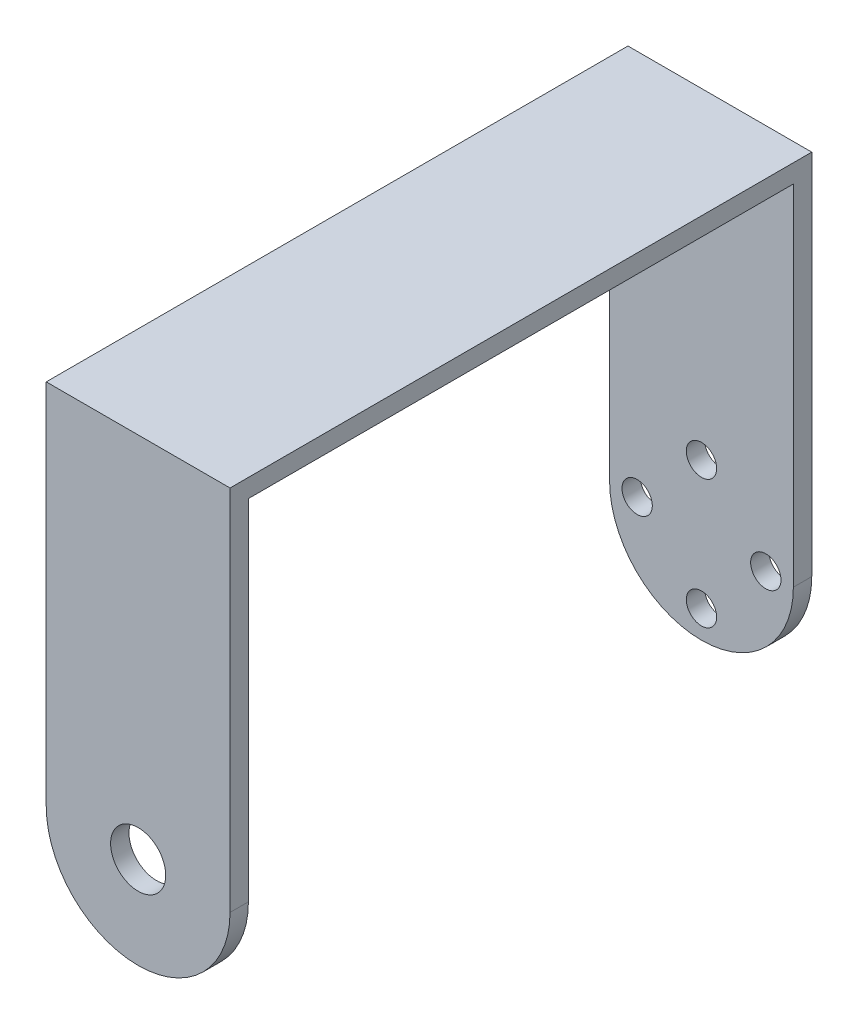
SolidWorks part; units mm, degrees
ref_plane "前视基准面" through (0, 0, 0) normal (0, 0, 1) x (1, 0, 0)
ref_plane "上视基准面" through (0, 0, 0) normal (0, 1, 0) x (1, 0, 0)
ref_plane "右视基准面" through (0, 0, 0) normal (1, 0, 0) x (0, 0, -1)
sketch "草图1" plane through (0, 0, 0) normal (0, 0, 1) x (1, 0, 0)
  line L2 (0, 0) -> (0, 40)
  line L3 (0, 40) -> (20, 40)
  line L4 (20, 0) -> (20, 40)
  arc A0 (20, 0) -> (0, 0) centre (10, 0) cw
  dimension "D1" = 20
  dimension "D2" = 40
extrude "凸台-拉伸1" add sketch "草图1" along normal blind 2
sketch "草图2" plane through (0, 0, 2) normal (0, 0, 1) x (1, 0, 0)
  line L0 (20, 0) -> (20, 40) construction
  line L1 (0, 40) -> (20, 40)
  line L2 (0, 40) -> (0, 38)
  line L3 (0, 38) -> (20, 38)
  line L4 (20, 40) -> (20, 38)
  dimension "D1" = 2
extrude "凸台-拉伸2" add sketch "草图2" along normal blind 61.3
sketch "草图3" plane through (0, 40, 0) normal (0, 1, 0) x (1, 0, 0)
  line L0 (0, -31.65) -> (20, -31.65) construction
  line L1 (0, -63.3) -> (0, 0) construction
  line L2 (20, -63.3) -> (20, 0) construction
ref_plane "基准面1" through (0, 0, 31.65) normal (0, 0, 1) x (1, 0, 0)
mirror "镜向1" about plane through (0, 0, 31.65) normal (0, 0, 1) of "凸台-拉伸1"
sketch "草图4" plane through (0, 0, 63.3) normal (0, 0, 1) x (1, 0, 0)
  line L0 (20, 0) -> (0, 0) construction
  circle A0 centre (10, 0) radius 3
  dimension "D1" = 6
  dimension "D2" = 10
extrude "切除-拉伸1" cut sketch "草图4" against normal up to next
sketch "草图5" plane through (0, 0, 0) normal (0, 0, -1) x (-1, 0, 0)
  line L0 (0, 0) -> (-20, 0) construction
  line L1 (-10, 0) -> (-10, -10) construction
  arc A0 (-20, 0) -> (0, 0) centre (-10, 0) ccw construction
  circle A1 centre (-10, -7) radius 1.65
  circle A2 centre (-17, 0) radius 1.65
  circle A3 centre (-10, 7) radius 1.65
  circle A4 centre (-3, 0) radius 1.65
  point P20 (-10, 0)
  dimension "D1" = 3.3
  dimension "D2" = 7
  dimension "D3" = 4
extrude "切除-拉伸2" cut sketch "草图5" against normal up to next
